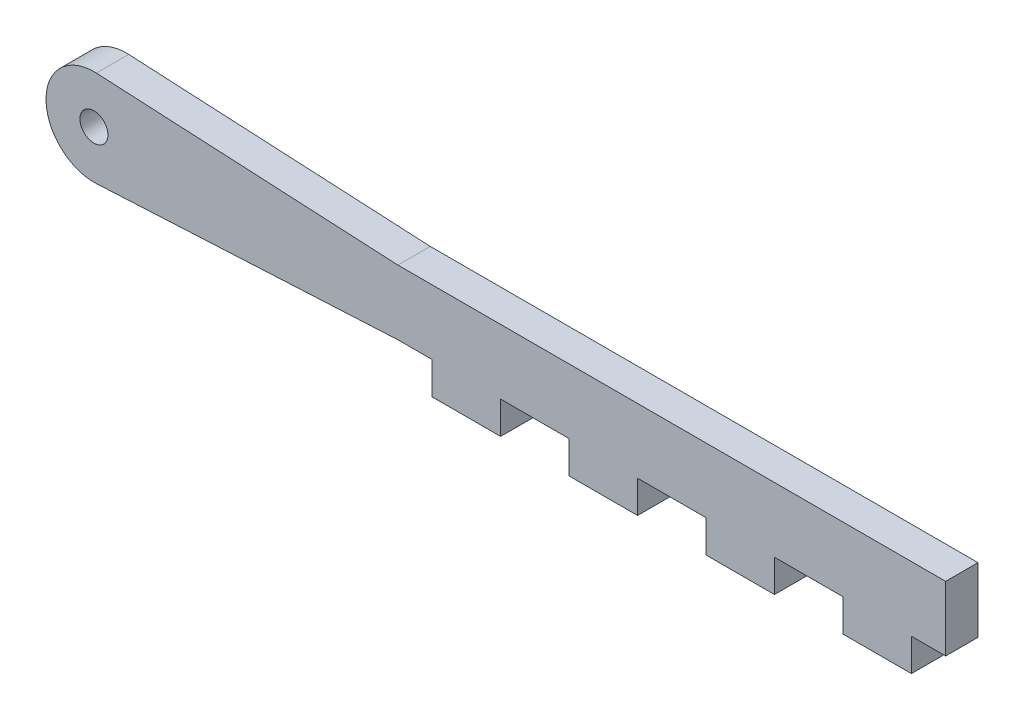
SolidWorks part; units mm, degrees
ref_plane "Front Plane" through (0, 0, 0) normal (0, 0, 1) x (1, 0, 0)
ref_plane "Top Plane" through (0, 0, 0) normal (0, 1, 0) x (1, 0, 0)
ref_plane "Right Plane" through (0, 0, 0) normal (1, 0, 0) x (0, 0, -1)
sketch "Sketch2" plane through (0, 0, 0) normal (0, 0, 1) x (1, 0, 0)
  line L0 (-28.194, 3) -> (0, 3) construction
  line L1 (0, 6) -> (-27.9656, 7.4391)
  line L2 (50.8, 0) -> (0, 0)
  line L3 (50.8, 0) -> (50.8, 6)
  line L4 (50.8, 6) -> (0, 6)
  line L5 (0, 0) -> (0, 3) construction
  line L6 (50.8, 0) -> (0, 6) construction
  line L7 (50.8, 6) -> (0, 0) construction
  line L8 (0, 0) -> (-27.9656, -1.4391)
  line L9 (0, 3) -> (0, 6) construction
  circle A0 centre (-28.194, 3) radius 1.3
  arc A1 (-27.9656, 7.4391) -> (-27.9656, -1.4391) centre (-28.194, 3) ccw
  arc A2 (-27.9656, -1.4391) -> (-23.749, 3) centre (-28.194, 3) ccw construction
  arc A3 (-23.749, 3) -> (-27.9656, 7.4391) centre (-28.194, 3) ccw construction
  point P3 (25.4, 3)
  dimension "D1" = 2.6
  dimension "D2" = 8.89
  dimension "D3" = 28.194
  dimension "D4" = 6
  dimension "D5" = 50.8
extrude "Boss-Extrude1" add sketch "Sketch2" along normal blind 3
sketch "Sketch3" plane through (0, 0, 0) normal (0, -1, 0) x (1, 0, 0)
  line L0 (0, 3) -> (50.8, 3) construction
  line L1 (3.175, 3) -> (9.525, 3)
  line L2 (3.175, 3) -> (3.175, 0)
  line L3 (3.175, 0) -> (9.525, 0)
  line L4 (9.525, 3) -> (9.525, 0)
  line L5 (0, 0) -> (50.8, 0) construction
  line L6 (0, 3) -> (0, 0) construction
  dimension "D1" = 3.175
  dimension "D2" = 6.35
extrude "Boss-Extrude2" add sketch "Sketch3" along normal blind 3
pattern_linear "LPattern1" count 4 spacing 12.7 along (1, 0, 0) of "Boss-Extrude2"
